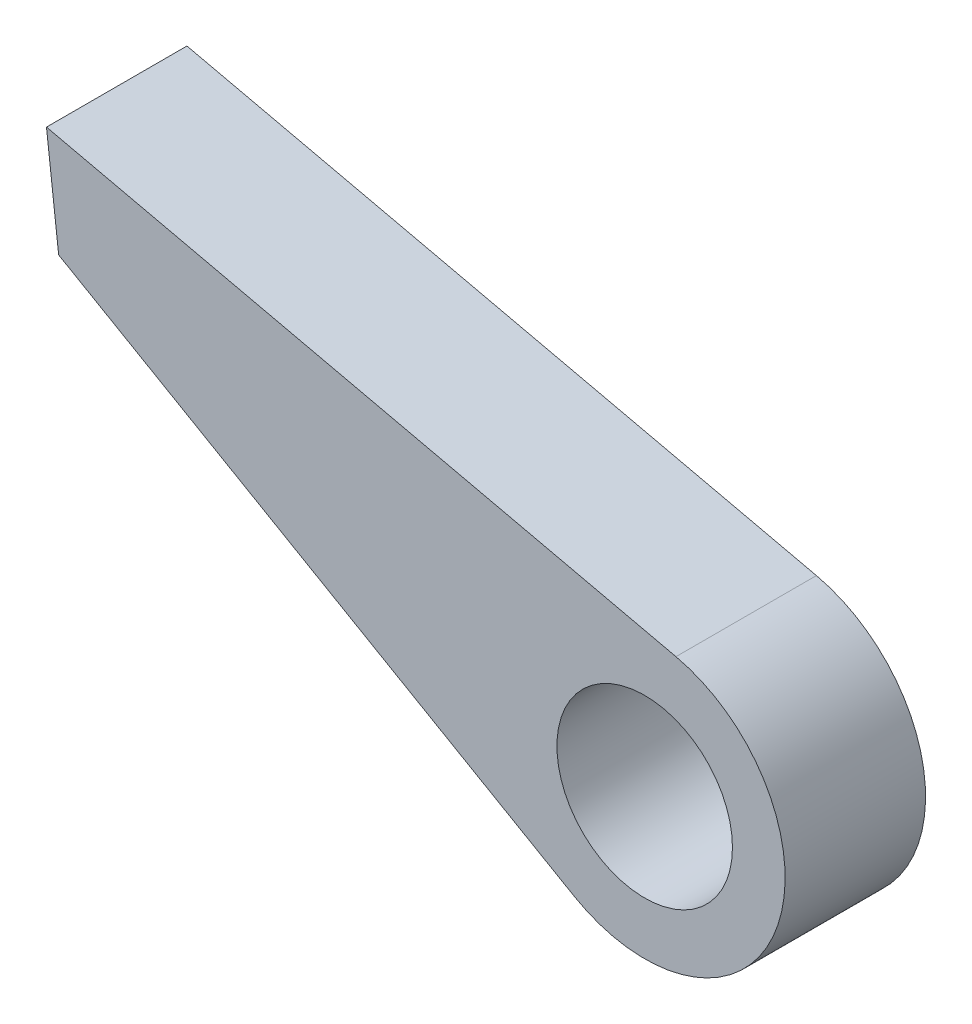
SolidWorks part; units mm, degrees
ref_plane "前视基准面" through (0, 0, 0) normal (0, 0, 1) x (1, 0, 0)
ref_plane "上视基准面" through (0, 0, 0) normal (0, 1, 0) x (1, 0, 0)
ref_plane "右视基准面" through (0, 0, 0) normal (1, 0, 0) x (0, 0, -1)
sketch "草图1" plane through (0, 0, 0) normal (0, 0, 1) x (1, 0, 0)
  line L0 (-1, -1.7321) -> (-8.3453, 2.5087)
  line L1 (-8.3453, 2.5087) -> (-8.5184, 3.9987)
  line L2 (-8.5184, 3.9987) -> (0.4457, 1.9497)
  line L3 (-5.3126, 0) -> (3.3713, 0) construction
  circle A2 centre (0, 0) radius 1.25
  arc A3 (-1, -1.7321) -> (0.4457, 1.9497) centre (0, 0) ccw
  point P3 (-8, 2.3094)
  point P4 (-8.5184, 3.9987)
  point P12 (0, 0)
  dimension "D1" = 4
  dimension "D2" = 2.5
  dimension "D3" = 8
  dimension "D4" = 1.5
  dimension "D5" = 30
extrude "凸台-拉伸1" add sketch "草图1" along normal blind 2
